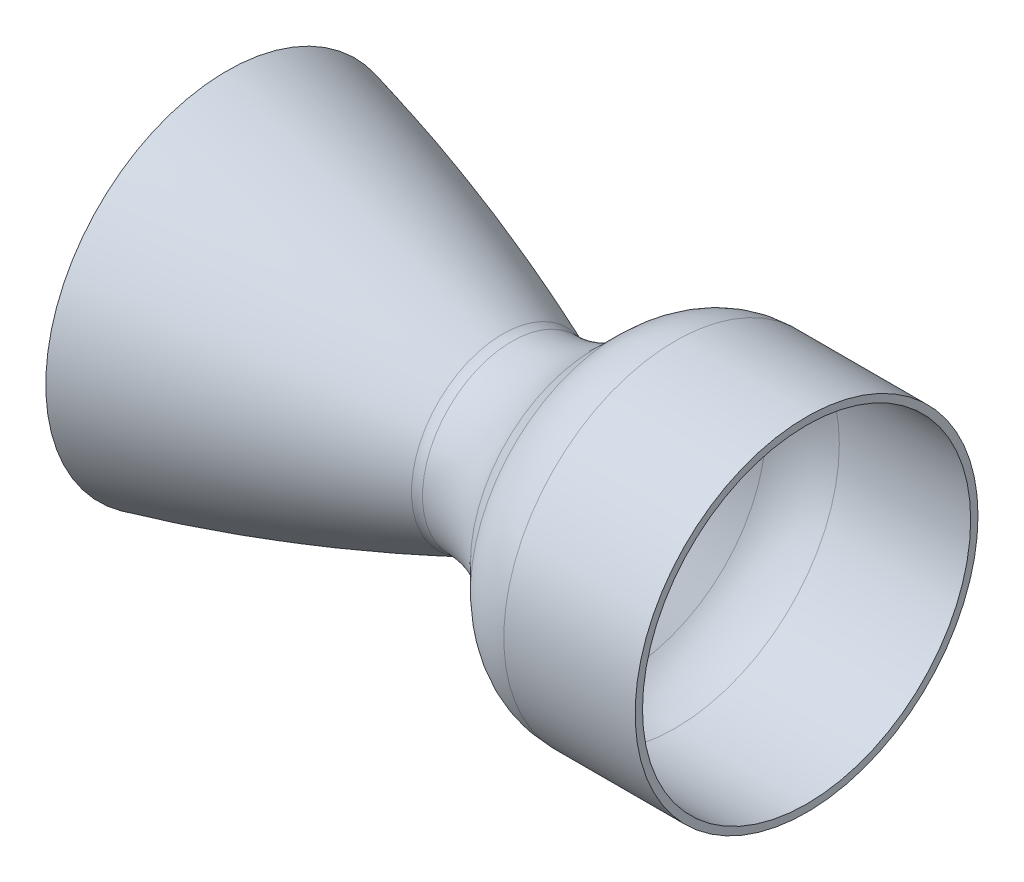
SolidWorks part; units mm, degrees
ref_plane "Front Plane" through (0, 0, 0) normal (0, 0, 1) x (1, 0, 0)
ref_plane "Top Plane" through (0, 0, 0) normal (0, 1, 0) x (1, 0, 0)
ref_plane "Right Plane" through (0, 0, 0) normal (1, 0, 0) x (0, 0, -1)
sketch "Sketch1" plane through (0, 0, 0) normal (0, 0, 1) x (1, 0, 0)
  line L0 (41.8608, 22.4) -> (23.9319, 22.4)
  line L1 (16.8608, 19.4711) -> (13.5104, 16.1206)
  line L3 (0, 0) -> (-234.9488, 0) construction
  line L8 (41.8608, 23.4) -> (23.9319, 23.4)
  line L12 (16.1537, 20.1782) -> (12.8033, 16.8277)
  line L13 (41.8608, 22.4) -> (41.8608, 23.4)
  line L14 (-37.496, 23.7588) -> (-37.2634, 24.7313)
  arc A0 (23.9319, 22.4) -> (16.8608, 19.4711) centre (23.9319, 12.4) ccw
  arc A4 (23.9319, 23.4) -> (16.1537, 20.1782) centre (23.9319, 12.4) ccw
  arc A8 (12.8033, 16.8277) -> (0.9753, 12.2136) centre (1.631, 28) cw construction
  arc A10 (0.7733, 11.2219) -> (0, 11.5231) centre (8.0159, 30.9626) cw construction
  arc A11 (13.5104, 16.1206) -> (0.7733, 11.2219) centre (1.631, 28) cw construction
  arc A12 (13.5104, 16.1206) -> (1.631, 11.2) centre (1.631, 28) cw
  arc A13 (1.631, 11.2) -> (0, 11.5231) centre (1.631, 15.4784) cw
  arc A14 (12.8033, 16.8277) -> (1.631, 12.2) centre (1.631, 28) cw
  arc A15 (0.3812, 12.4476) -> (1.631, 12.2) centre (1.631, 15.4784) ccw
  arc A16 (0.9753, 12.2136) -> (0.3812, 12.4476) centre (8.0159, 30.9626) cw construction
  spline S0 degree 2 poles (0, 11.5231) (-18.8638, 19.3016) (-37.496, 23.7588) knots 0 0 0 1 1 1 construction
  spline S1 degree 1 poles (0.3812, 12.4476) (-37.2634, 24.7313) knots 0 0 1 1 construction
  spline S2 degree 2 poles (0, 11.5231) (-18.8638, 19.3016) (-37.496, 23.7588) knots 0 0 0 1 1 1
  spline S3 degree 2 poles (0.3812, 12.4476) (-18.5503, 20.2544) (-37.2634, 24.7313) knots 0 0 0 1 1 1
  dimension "D1" = 10
  dimension "D4" = 16.8
  dimension "D5" = 4.2784
  dimension "D14" = 22.4
  dimension "D16" = 25
  dimension "D2" = 11.2
  dimension "D6" = 45
  dimension "D7" = 23.7588
  dimension "D3" = 1
revolve "Revolve1" add sketch "Sketch1" angle 360 about L3
equation "\"theta_t\"= 36.9009 - ( 426.271 / ( \"Aet\" + 7.00037 ) ) + ( 10026.8 / ( \"Aet\" + 7.00037 ) ^ 2 ) - ( 175410 / ( \"Aet\" + 7.00037 ) ^ 3 ) + ( ( 1.6742 * ( 10 ^ 6 ) ) / ( \"Aet\" + 7.00037 ) ^ 4 ) - ( ( 6.7643 * ( 10 ^ 6 ) ) / ( \"Aet\" + 7.00037 ) ^ 5 )"
equation "\"rt\"= 11.2"
equation "\"re\"= sqr ( \"rt\" ^ 2 * \"Aet\" )"
equation "\"Aet\" = 4.5"
equation "\"L\"= 0.8 * ( ( \"re\" / tan ( 15 ) ) - ( \"rt\" / tan ( 15 ) ) )"
equation "\"lc\"= ( \"l*\" / \"cr\" )"
equation "\"b\"= tan ( \"theta_t\" )"
equation "\"a\"= ( \"re\" - \"b\" * \"L\" - \"c\" ) / \"L\" ^ 2"
equation "\"c\"= \"rt\" * ( 1.382 - 0.382 * cos ( \"theta_t\" ) )"
equation "\"cr\"= 4"
equation "\"rc\"= sqr ( \"cr\" * ( \"rt\" ^ 2 ) )"
equation "\"D14@Sketch1\"=\"rc\""
equation "\"l*\"= 100"
equation "\"D16@Sketch1\"=\"lc\""
equation "\"th\"= 1"
equation "\"theta_cr\"= 45deg"
equation "\"theta_e\"= 5.48 + ( 134.316 / ( \"Aet\" + 1.49269 ) ) - ( 1742.02 / ( \"Aet\" + 1.49269 ) ^ 2 ) + ( 13091 / ( \"Aet\" + 1.49269 ) ^ 3 ) - ( 41929.9 / ( \"Aet\" + 1.49269 ) ^ 4 ) + ( 44445.1 / ( \"Aet\" + 1.49269 ) ^ 5 )"
equation "\"Nx\"= 0"
equation "\"Ny\"= \"c\""
equation "\"Qx\"= ( \"re\" - ( tan ( \"theta_e\" ) * \"L\" ) - \"c\" ) / ( tan ( \"theta_t\" ) - tan ( \"theta_e\" ) )"
equation "\"Qy\"= tan ( \"theta_t\" ) * \"Qx\" + \"c\""
equation "\"Ex\"= \"L\""
equation "\"Ey\"= \"re\""
equation "\"D3@Sketch1\"=\"th\""
equation "\"D2@Sketch1\"=\"rt\""
equation "\"D4@Sketch1\"=\"rt\"*1.5"
equation "\"D5@Sketch1\"=\"rt\"*0.382"
equation "\"D6@Sketch1\"=\"theta_cr\""
equation "\"D7@Sketch1\"=\"re\""
